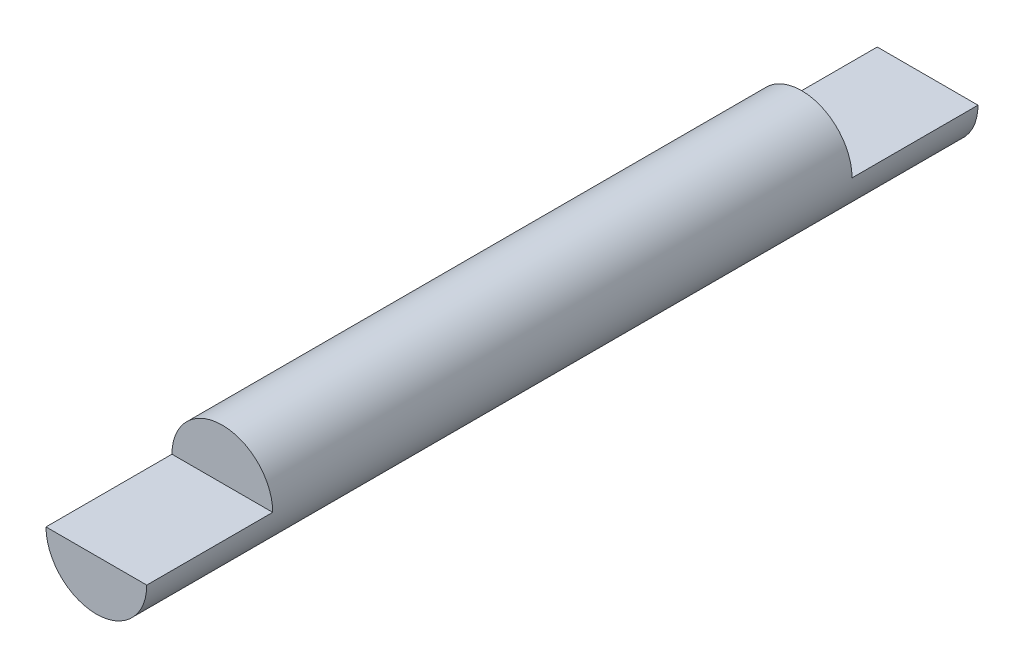
SolidWorks part; units mm, degrees
ref_plane "Plan de face" through (0, 0, 0) normal (0, 0, 1) x (1, 0, 0)
ref_plane "Plan de dessus" through (0, 0, 0) normal (0, 1, 0) x (1, 0, 0)
ref_plane "Plan de droite" through (0, 0, 0) normal (1, 0, 0) x (0, 0, -1)
sketch "Esquisse1" plane through (0, 0, 0) normal (0, 0, 1) x (1, 0, 0)
  circle A0 centre (0, 0) radius 2
  dimension "D1" = 4
extrude "Boss.-Extru.1" add sketch "Esquisse1" along normal blind 33
sketch "Esquisse2" plane through (0, 0, 0) normal (0, 0, -1) x (-1, 0, 0)
  line L0 (-2, 0) -> (2, 0)
  line L1 (-2, 0) -> (-2, 3)
  line L2 (2, 0) -> (2, 3)
  line L3 (-2, 3) -> (2, 3)
  circle A0 centre (0, 0) radius 2 construction
  dimension "D1" = 3
extrude "Enlèv. mat.-Extru.1" cut sketch "Esquisse2" against normal blind 5
ref_plane "Plan1" through (0, 0, 16.5) normal (0, 0, 1) x (1, 0, 0)
mirror "Symétrie1" about plane through (0, 0, 16.5) normal (0, 0, 1) of "Enlèv. mat.-Extru.1"
